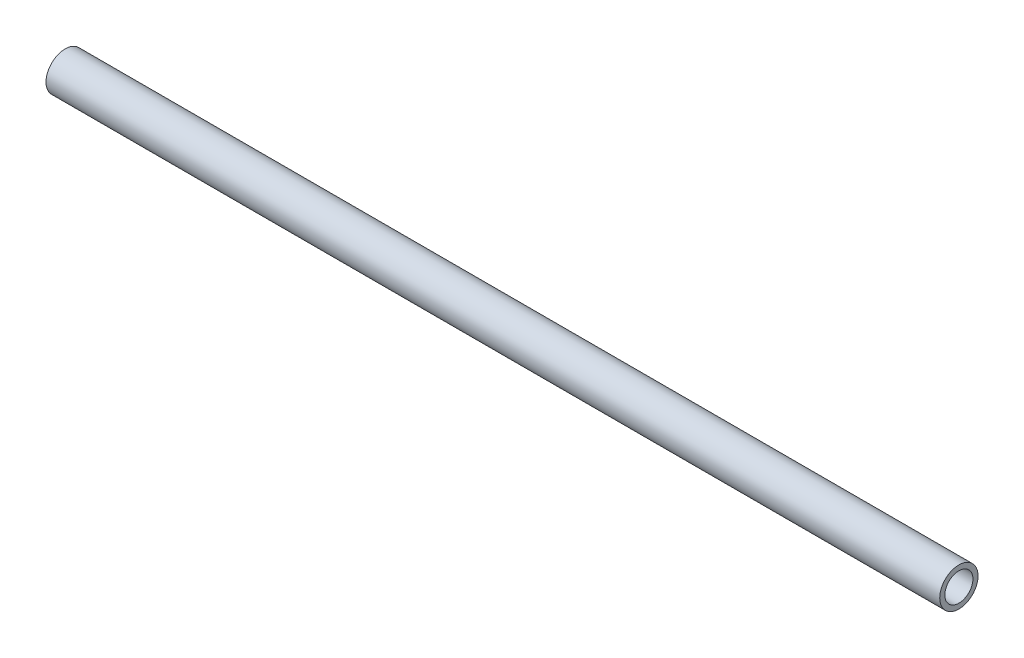
SolidWorks part; units mm, degrees
ref_plane "Front Plane" through (0, 0, 0) normal (0, 0, 1) x (1, 0, 0)
ref_plane "Top Plane" through (0, 0, 0) normal (0, 1, 0) x (1, 0, 0)
ref_plane "Right Plane" through (0, 0, 0) normal (1, 0, 0) x (0, 0, -1)
sketch "Axial profile (mm)" plane through (0, 0, 0) normal (0, 0, 1) x (1, 0, 0)
  line L0 (-110, 0) -> (75, 0) construction
  line L1 (13.7, 1.65) -> (118.7, 1.65)
  line L2 (118.7, 1.65) -> (118.7, 2.25)
  line L3 (118.7, 2.25) -> (13.7, 2.25)
  line L4 (13.7, 2.25) -> (13.7, 1.65)
revolve "Full revolution" add sketch "Axial profile (mm)" angle 360 about L0
